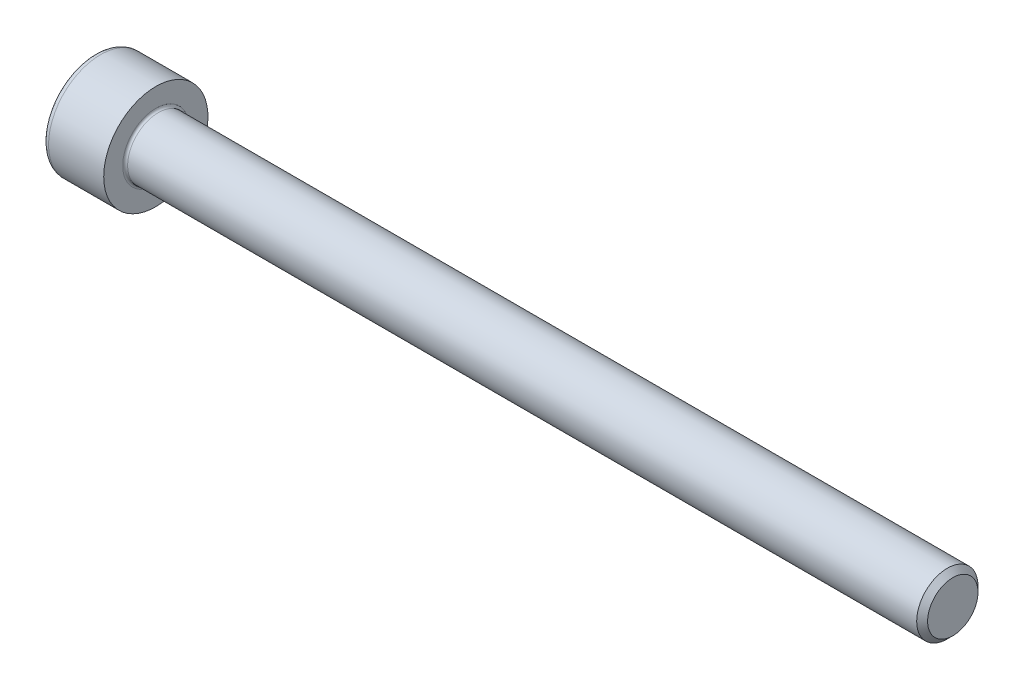
SolidWorks part; units mm, degrees
revolve "Base-Revolve" add sketch "BodySke"
sketch "BodySke" plane through (0, 0, 0) normal (0, 0, 1) x (1, 0, 0)
  line L0 (0, 0) -> (0, 4.25)
  line L1 (0, 4.25) -> (5, 4.25)
  line L2 (5, 4.25) -> (5, 2.5)
  line L3 (5, 2.5) -> (69.555, 2.5)
  line L4 (70, 2.055) -> (70, 0)
  line L5 (70, 0) -> (0, 0)
  line L6 (-31.75, 0) -> (127, 0) construction
  line L8 (70, 2.055) -> (69.555, 2.5)
  line L10 (70, -2.055) -> (69.555, -2.5) construction
  line L11 (5.8, 9.525) -> (5.8, 3.175) construction
  line L12 (45, 9.525) -> (45, 3.175) construction
  line L13 (5, 9.525) -> (5, 3.175) construction
  dimension "Head_ht" = 5
  dimension "Length" = 65
  dimension "Body_ch_ang" = 45
  dimension "Diameter" = 5
  dimension "Minor_dia" = 4.11
  dimension "Advance" = 0.8
  dimension "Thread_nom" = 25
  dimension "Thread_length" = 65
  dimension "Head_dia" = 8.5
cosmetic thread "ThreadCosmetic"
fillet "Fillet1" radius 0.2 1 edges at (5, 0, 2.5)
fillet "Fillet2" radius 0.5 1 edges at (0, 0, 4.25)
ref_plane "Plane1" through (0, 0, 0) normal (0, 0, 1) x (1, 0, 0)
ref_plane "Plane2" through (0, 0, 0) normal (0, 1, 0) x (1, 0, 0)
ref_plane "Plane3" through (0, 0, 0) normal (1, 0, 0) x (0, 0, -1)
sketch "Sketch2" plane through (0, 0, 0) normal (0, 0, 1) x (1, 0, 0)
  line L0 (0, 2.01) -> (2.5, 2.01)
  line L1 (2.5, 2.01) -> (3.6605, 0)
  line L2 (-31.75, 0) -> (127, 0) construction
  line L3 (3.6605, 0) -> (0, 0)
  line L4 (0, 0) -> (0, 2.01)
  line L6 (0, 0) -> (47.625, 0) construction
  dimension "D1" = 2.01
  dimension "D2" = 60
  dimension "Depth" = 2.5
revolve "Hex-PreBroach" cut sketch "Sketch2" angle 360 about L6
sketch "Sketch3" plane through (0, 0, 0) normal (-1, 0, 0) x (0, 0.5, 0.866)
  line L0 (1.1605, 2.01) -> (-1.1605, 2.01)
  line L1 (-1.1605, 2.01) -> (-2.3209, 0)
  line L2 (1.1605, 2.01) -> (2.3209, 0)
  line L3 (1.1605, -2.01) -> (2.3209, 0)
  line L4 (1.1605, -2.01) -> (-1.1605, -2.01)
  line L5 (-1.1605, -2.01) -> (-2.3209, 0)
  dimension "D1" = 2.01
  dimension "D2" = 2.01
  dimension "Hex_size" = 4.02
extrude "Hex" cut sketch "Sketch3" against normal blind 2.5
sketch "ThdSchSke" plane through (0, 0, 0) normal (0, 0, 1) x (1, 0, 0)
  line L0 (45, -2.055) -> (44.6884, -2.5)
  line L1 (45, -2.055) -> (45.3116, -2.5)
  line L2 (45.3116, -2.5) -> (45.3116, -3.125)
  line L3 (-3.175, 0) -> (5.1513, 0) construction
  line L4 (0, 3.75) -> (0, -3.75) construction
  line L5 (45.3116, -3.125) -> (44.6884, -3.125)
  line L6 (44.6884, -3.125) -> (44.6884, -2.5)
  dimension "Thread_minor" = 4.11
  dimension "Diameter" = 5
  dimension "Start" = 45
revolve "ThreadSchematic" [suppressed] cut sketch "ThdSchSke" angle 360 about L3
pattern_linear "ThdSchPat" [suppressed]
equation "\"D2@Sketch3\" = \"Hex_size@Sketch3\" / 2"
equation "\"D1@Sketch3\" = \"Hex_size@Sketch3\" / 2"
equation "\"D1@Sketch2\" = \"Hex_size@Sketch3\" / 2"
equation "\"Thread_minor@ThreadCosmetic\"  =  \"Minor_dia@BodySke\""
equation "\"Depth@Sketch2\" =  \"Key_eng@Hex\""
equation "\"Thread_length@ThreadCosmetic\" = ((sgn( (\"Length@BodySke\" - \"Advance@BodySke\" * 3.0) - \"Thread_nom@BodySke\" )-1)*( (\"Length@BodySke\" - \"Advance@BodySke\" * 3.0) - \"Thread_nom@BodySke\" ))/-2+ \"Thread_nom@BodySke\""
equation "\"Thread_minor@ThdSchSke\" = \"Minor_dia@BodySke\""
equation "\"Diameter@ThdSchSke\" = \"Diameter@BodySke\""
equation "\"Overcut@ThdSchSke\" = \"Diameter@BodySke\" * 1.25"
equation "\"Start@ThdSchSke\" = \"Head_ht@BodySke\" + \"Length@BodySke\" - \"Thread_length@ThreadCosmetic\"  '---Non-countersunk---"
equation "\"Num_threads@ThdSchPat\" = int( \"Thread_length@ThreadCosmetic\" / \"Advance@BodySke\" + 0.999 )  + 1"
equation "\"Advance@ThdSchPat\" = \"Thread_length@ThreadCosmetic\" /  (\"Num_threads@ThdSchPat\" - 1) 'relax it"
equation "\"Num_threads@ThdSchPat\" = \"Num_threads@ThdSchPat\" - sgn( \"Num_threads@ThdSchPat\" - 1) '---chamfered tips only---"
